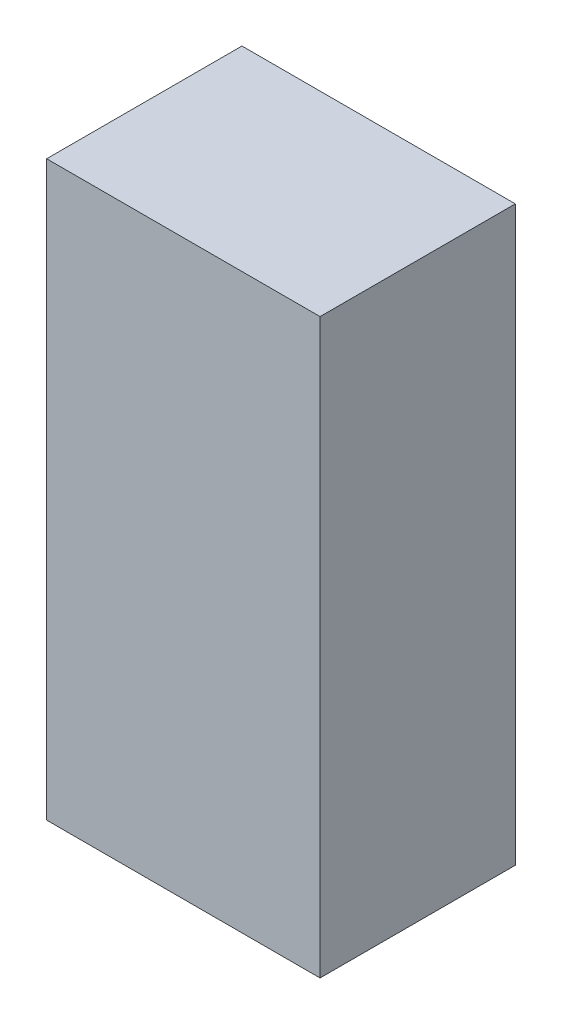
SolidWorks part; units mm, degrees
ref_plane "前视基准面" through (0, 0, 0) normal (0, 0, 1) x (1, 0, 0)
ref_plane "上视基准面" through (0, 0, 0) normal (0, 1, 0) x (1, 0, 0)
ref_plane "右视基准面" through (0, 0, 0) normal (1, 0, 0) x (0, 0, -1)
other "Configuration Table"
sketch "草图1" plane through (0, 0, 0) normal (0, 0, 1) x (1, 0, 0)
  line L0 (0, 0) -> (21, 0)
  line L1 (21, 0) -> (21, 44)
  line L2 (21, 44) -> (0, 44)
  line L3 (0, 44) -> (0, 0)
  dimension "width" = 21
  dimension "height" = 44
extrude "Side_adapter" add sketch "草图1" along normal blind 15
